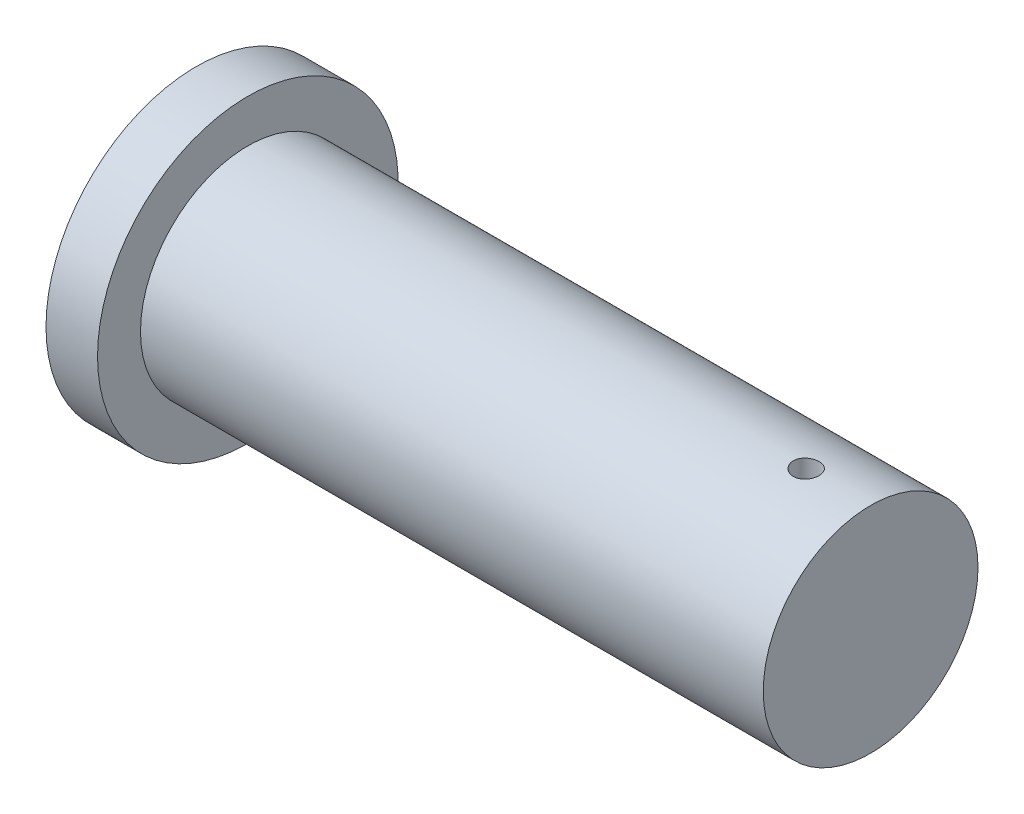
SolidWorks part; units mm, degrees
ref_plane "Front Plane" through (0, 0, 0) normal (0, 0, 1) x (1, 0, 0)
ref_plane "Top Plane" through (0, 0, 0) normal (0, 1, 0) x (1, 0, 0)
ref_plane "Right Plane" through (0, 0, 0) normal (1, 0, 0) x (0, 0, -1)
sketch "Sketch1" plane through (0, 0, 0) normal (0, 0, 1) x (1, 0, 0)
  line L0 (0, 0) -> (0, 25)
  line L1 (0, 25) -> (-145, 25)
  line L2 (-145, 25) -> (-145, 35)
  line L3 (-145, 35) -> (-157, 35)
  line L4 (-157, 35) -> (-157, 0)
  line L5 (-157, 0) -> (0, 0)
  dimension "D1" = 25
  dimension "D2" = 35
  dimension "D3" = 12
  dimension "D4" = 157
revolve "Revolve1" add sketch "Sketch1" angle 360 about L5
sketch "Sketch2" plane through (0, 0, 0) normal (0, 1, 0) x (1, 0, 0)
  line L0 (-145, -25) -> (-145, 25) construction
  circle A0 centre (-15, 0) radius 3
  point P4 (0, 0)
  dimension "D1" = 6
  dimension "D2" = 130
extrude "Cut-Extrude1" cut sketch "Sketch2" against normal through all and the other way through all
